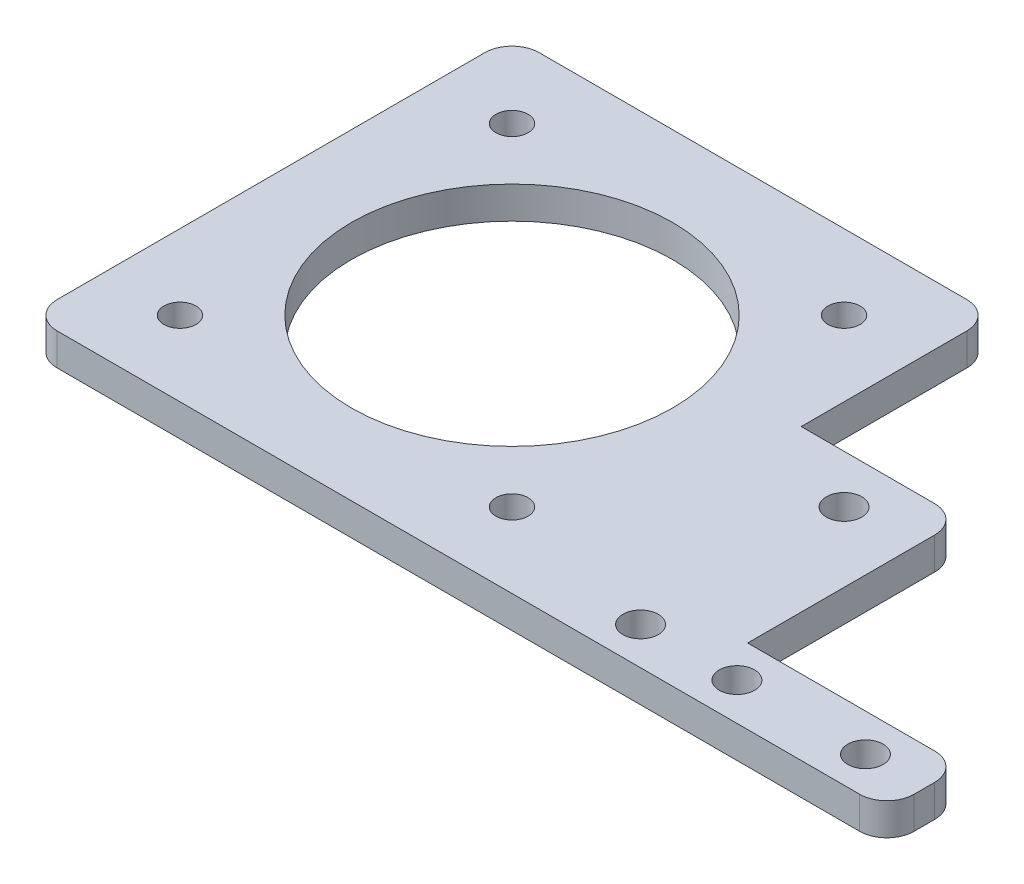
SolidWorks part; units mm, degrees
material "ABS"
ref_plane "Front Plane" through (0, 0, 0) normal (0, 0, 1) x (1, 0, 0)
ref_plane "Top Plane" through (0, 0, 0) normal (0, 1, 0) x (1, 0, 0)
ref_plane "Right Plane" through (0, 0, 0) normal (1, 0, 0) x (0, 0, -1)
sketch "Sketch1" plane through (0, 0, 0) normal (0, 1, 0) x (1, 0, 0)
  line L5 (0, 0) -> (15.5, 15.5) construction
  line L10 (0, 0) -> (31, 0) construction
  line L20 (31, 0) -> (31, -19) construction
  line L21 (31, -19) -> (40, -19) construction
  line L22 (40, -19) -> (52, -19) construction
  line L23 (22.5, -22.5) -> (57.5, -22.5)
  line L24 (-22.5, -22.5) -> (22.5, -22.5)
  line L25 (-22.5, -22.5) -> (-22.5, 22.5)
  line L26 (-22.5, 22.5) -> (22.5, 22.5)
  line L28 (-22.5, -22.5) -> (22.5, 22.5) construction
  line L29 (-22.5, 22.5) -> (22.5, -22.5) construction
  line L30 (57.5, -22.5) -> (57.5, -15.5)
  line L31 (57.5, -15.5) -> (37.5, -15.5)
  line L32 (37.5, -15.5) -> (37.5, 4.5)
  line L33 (37.5, 4.5) -> (22.5, 4.5)
  line L34 (22.5, 4.5) -> (22.5, 22.5)
  circle A15 centre (0, 0) radius 15
  circle A16 centre (15.5, 15.5) radius 1.5
  circle A17 centre (15.5, -15.5) radius 1.5
  circle A18 centre (-15.5, -15.5) radius 1.5
  circle A19 centre (-15.5, 15.5) radius 1.5
  circle A20 centre (31, 0) radius 1.65
  circle A21 centre (31, -19) radius 1.65
  circle A22 centre (40, -19) radius 1.65
  circle A23 centre (52, -19) radius 1.65
  point P17 (0, 0)
  dimension "D3" = 15.5
  dimension "D4" = 15.5
  dimension "D5" = 4
  dimension "D6" = 31
  dimension "D14" = 45
  dimension "D11" = 3.3
  dimension "D12" = 12
  dimension "D13" = 3.3
  dimension "D17" = 35
  dimension "D16" = 45
  dimension "D1" = 30
  dimension "D2" = 3
  dimension "D7" = 3.3
  dimension "D9" = 3.3
  dimension "D8" = 19
  dimension "D10" = 9
  dimension "D15" = 45
  dimension "D18" = 20
  dimension "D19" = 20
extrude "Main Body" add sketch "Sketch1" along normal blind 3
fillet "FIllet" radius 2.54 6 edges at (-22.5, 1.5, 22.5) (57.5, 1.5, 22.5) (57.5, 1.5, 15.5) (37.5, 1.5, -4.5) (22.5, 1.5, -22.5) (-22.5, 1.5, -22.5)
